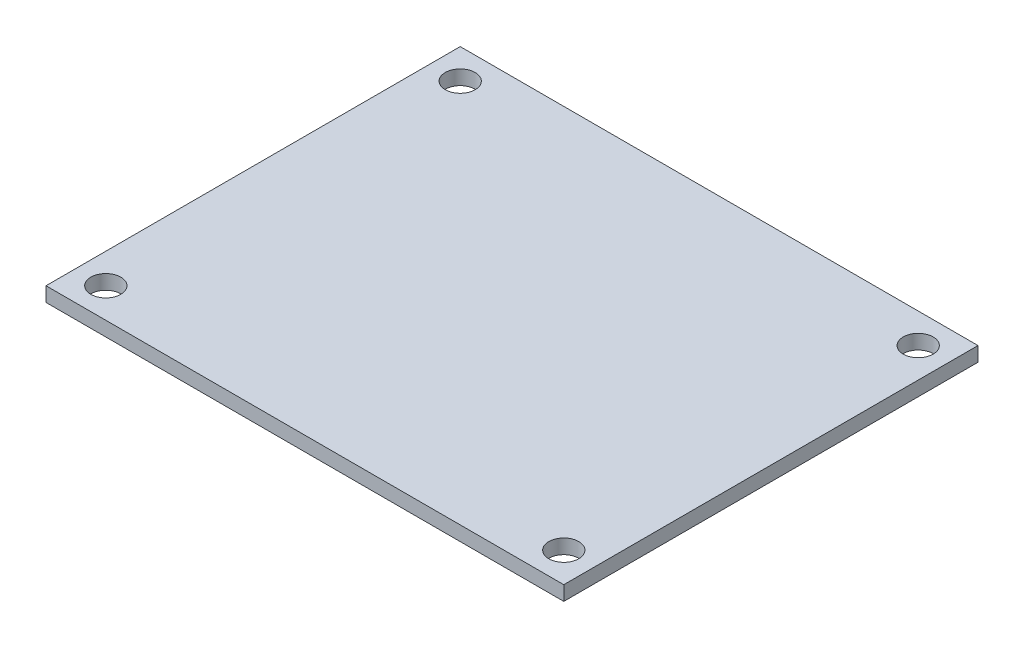
SolidWorks part; units mm, degrees
ref_plane "Front Plane" through (0, 0, 0) normal (0, 0, 1) x (1, 0, 0)
ref_plane "Top Plane" through (0, 0, 0) normal (0, 1, 0) x (1, 0, 0)
ref_plane "Right Plane" through (0, 0, 0) normal (1, 0, 0) x (0, 0, -1)
sketch "Sketch1" plane through (0, 0, 0) normal (0, 1, 0) x (1, 0, 0)
  line L1 (1.2631, -22.423) -> (58.4131, -22.423)
  line L2 (1.2631, -22.423) -> (1.2631, 23.297)
  line L3 (1.2631, 23.297) -> (58.4131, 23.297)
  line L4 (58.4131, -22.423) -> (58.4131, 23.297)
  line L5 (1.2631, -22.423) -> (58.4131, 23.297) construction
  line L6 (1.2631, 23.297) -> (58.4131, -22.423) construction
  point P4 (29.8381, 0.437)
extrude "Boss-Extrude1" add sketch "Sketch1" along normal blind 1.6 contours L2 L1 L4 L3
sketch "Sketch2" plane through (0, 1.6, 0) normal (0, 1, 0) x (1, 0, 0)
  line L0 (1.2631, 23.297) -> (58.4131, 23.297) construction
  line L1 (1.2631, -22.423) -> (1.2631, 23.297) construction
  circle A0 centre (4.5631, 19.997) radius 1.65
  dimension "D1" = 3.3
  dimension "D2" = 3.3
  dimension "D3" = 3.3
extrude "Cut-Extrude1" cut sketch "Sketch2" against normal through all
ref_plane "Plane1" through (0, 0, -0.437) normal (0, 0, 1) x (1, 0, 0)
ref_plane "Plane2" through (29.8381, 0, 0) normal (-1, 0, 0) x (0, 0, 1)
mirror "Mirror1" about plane through (0, 0, -0.437) normal (0, 0, 1) of "Cut-Extrude1"
mirror "Mirror3" about plane through (29.8381, 0, 0) normal (-1, 0, 0) of "Mirror1", "Cut-Extrude1"
equation "\"MDF\"= 4.8mm"
equation "\"Foamcore\"= 4.6mm"
equation "\"PCB\" = 1.6mm"
equation "\"GMaterial\"= \"MDF\""
equation "\"D1@Boss-Extrude1\"=\"PCB\""
